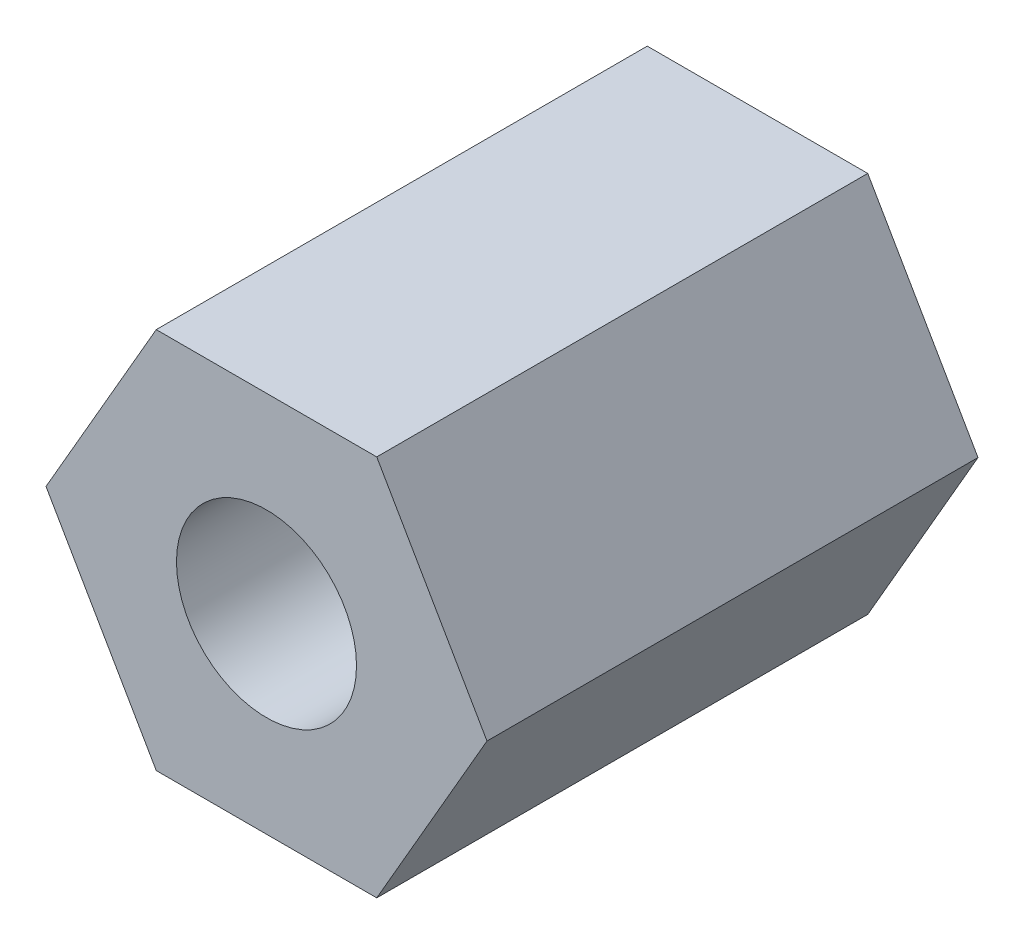
SolidWorks part; units mm, degrees
material "黃銅"
ref_plane "前基準面" through (0, 0, 0) normal (0, 0, 1) x (1, 0, 0)
ref_plane "上基準面" through (0, 0, 0) normal (0, 1, 0) x (1, 0, 0)
ref_plane "右基準面" through (0, 0, 0) normal (1, 0, 0) x (0, 0, -1)
sketch "草圖1" plane through (0, 0, 0) normal (0, 0, 1) x (1, 0, 0)
  line L1 (-2.0207, 3.5) -> (-4.0415, 0)
  line L2 (-4.0415, 0) -> (-2.0207, -3.5)
  line L3 (-2.0207, -3.5) -> (2.0207, -3.5)
  line L4 (2.0207, -3.5) -> (4.0415, 0)
  line L5 (4.0415, 0) -> (2.0207, 3.5)
  line L6 (2.0207, 3.5) -> (-2.0207, 3.5)
  circle A0 centre (0, 0) radius 3.5 construction
  dimension "D1" = 7
extrude "填料-伸長1" add sketch "草圖1" along normal blind 9
hole_wizard "M4x0.7 螺紋孔1" positions "草圖2" profile "草圖3" tap size "M4x0.7" standard "Ansi Metric" end condition through all
sketch "草圖2" plane through (0, 0, 9) normal (0, 0, 1) x (1, 0, 0)
  point P0 (0, 0)
sketch "草圖3" plane through (0, 0, 9) normal (1, 0, 0) x (0, -1, 0)
  line L0 (0, 0) -> (0, 9)
  line L1 (0, 9) -> (1.65, 9)
  line L2 (1.65, 9) -> (1.65, 0)
  line L5 (1.65, 0) -> (0, 0)
  line L11 (0, -6.35) -> (0, 107.95) construction
  dimension "貫穿螺孔鑽直徑" = 3.3
  dimension "貫穿螺孔鑽深度" = 9
